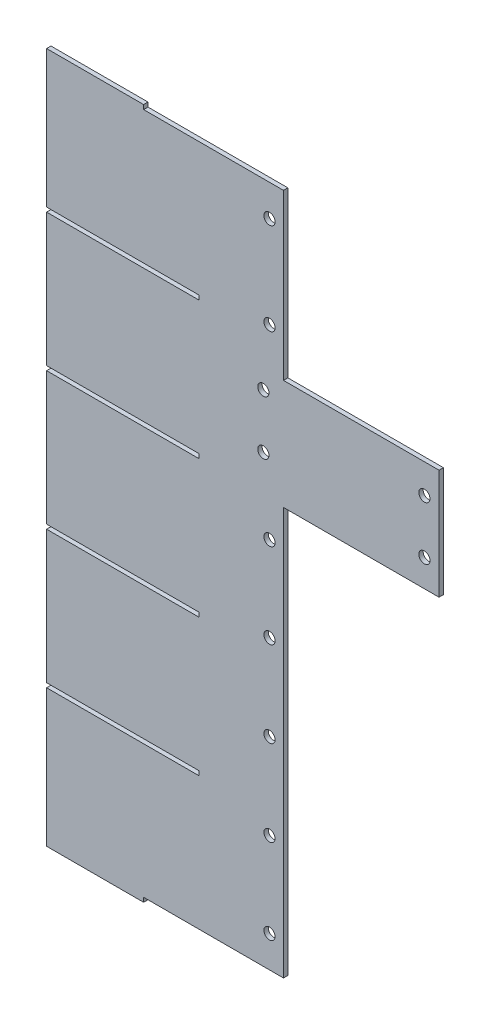
SolidWorks part; units mm, degrees
material "6061-T6 (SS)"
ref_plane "X-Y Datum" through (0, 0, 0) normal (0, 0, 1) x (1, 0, 0)
ref_plane "X-Z Datum" through (0, 0, 0) normal (0, 1, 0) x (1, 0, 0)
ref_plane "Y-Z Datum" through (0, 0, 0) normal (1, 0, 0) x (0, 0, -1)
sketch "Sketch1" plane through (0, 0, 0) normal (0, 0, 1) x (1, 0, 0)
  line L1 (129.0131, 254.2454) -> (-18.6854, 254.2454)
  line L3 (129.0131, -241.3467) -> (-18.6854, -241.3467)
  line L4 (-18.6854, 254.2454) -> (-18.6854, 157.667)
  line L24 (129.0131, 254.2454) -> (129.0131, -241.3467)
  line L25 (92.0885, 157.667) -> (-18.6854, 157.667)
  line L27 (92.0885, 154.492) -> (-18.6854, 154.492)
  line L29 (92.0885, 57.9136) -> (-18.6854, 57.9136)
  line L31 (92.0885, 54.7386) -> (-18.6854, 54.7386)
  line L33 (92.0885, -41.8399) -> (-18.6854, -41.8399)
  line L35 (92.0885, -45.0149) -> (-18.6854, -45.0149)
  line L37 (92.0885, -141.5933) -> (-18.6854, -141.5933)
  line L39 (92.0885, -144.7683) -> (-18.6854, -144.7683)
  line L41 (92.0885, -141.5933) -> (92.0885, -144.7683)
  line L42 (92.0885, -41.8399) -> (92.0885, -45.0149)
  line L43 (92.0885, 57.9136) -> (92.0885, 54.7386)
  line L44 (-18.6854, -144.7683) -> (-18.6854, -241.3467)
  line L45 (-18.6854, -45.0149) -> (-18.6854, -141.5933)
  line L46 (-18.6854, 54.7386) -> (-18.6854, -41.8399)
  line L47 (-18.6854, 154.492) -> (-18.6854, 57.9136)
  line L48 (92.0885, 157.667) -> (92.0885, 154.492)
extrude "Boss-Extrude2" add sketch "Sketch1" along normal blind 3.175
sketch "Sketch4" plane through (0, 0, 3.175) normal (0, 0, 1) x (1, 0, 0)
  line L0 (129.0131, 254.2454) -> (153.4072, 240.1614) construction
  line L2 (129.0131, 254.2454) -> (129.0131, -241.3467)
  line L4 (153.4072, 240.1614) -> (153.4072, -227.2627)
  line L6 (153.4072, -227.2627) -> (153.4072, -241.3467)
  line L7 (153.4072, -241.3467) -> (129.0131, -241.3467)
  line L8 (129.0131, 254.2454) -> (153.4072, 254.2454)
  line L9 (153.4072, 254.2454) -> (153.4072, 240.1614)
extrude "Boss-Extrude3" add sketch "Sketch4" against normal through all
sketch "Sketch7" plane through (0, 0, 3.175) normal (0, 0, 1) x (1, 0, 0)
  line L0 (51.8072, -241.3467) -> (-18.6854, -241.3467)
  line L1 (51.8072, -244.5217) -> (51.8072, -241.3467)
  line L2 (153.4072, -244.5217) -> (51.8072, -244.5217)
  line L3 (153.4072, -244.5217) -> (153.4072, -257.2217)
  line L4 (153.4072, -257.2217) -> (30.4963, -257.2217)
  line L5 (30.4963, -257.2217) -> (6.7146, -273.4777)
  line L6 (-18.6854, -273.4777) -> (6.7146, -273.4777)
  line L7 (-18.6854, -241.3467) -> (-18.6854, -273.4777)
  point P0 (-51.634, -260.9767)
  point P9 (-18.6854, -241.3467)
extrude "Boss-Extrude6" [suppressed] add sketch "Sketch7" against normal through all
sketch "Sketch8" [suppressed] plane through (0, 0, 3.175) normal (0, 0, 1) x (1, 0, 0)
  line L1 (153.4072, -257.2217) -> (221.7231, -257.2217)
  line L2 (153.4072, -257.2217) -> (153.4072, -244.5217)
  line L3 (153.4072, -244.5217) -> (221.7231, -244.5217)
  line L4 (221.7231, -257.2217) -> (221.7231, -244.5217)
  line L5 (153.4072, -241.3467) -> (221.7231, -241.3467)
  line L6 (153.4072, -241.3467) -> (153.4072, -144.7683)
  line L7 (153.4072, -144.7683) -> (221.7231, -144.7683)
  line L8 (221.7231, -241.3467) -> (221.7231, -144.7683)
  dimension "D1" = 68.3158
extrude "Boss-Extrude7" [suppressed] add sketch "Sketch8" against normal through all
sketch "Sketch11" plane through (0, 0, 3.175) normal (0, 0, 1) x (1, 0, 0)
  line L0 (92.0885, 54.7386) -> (153.4072, 54.7386) construction
  line L1 (153.4072, 134.68) -> (266.4372, 134.68)
  line L2 (153.4072, -241.3467) -> (153.4072, 254.2454) construction
  line L3 (266.4372, 134.68) -> (266.4372, 54.7386)
  line L4 (266.4372, 54.7386) -> (153.4072, 54.7386)
  line L5 (153.4072, 54.7386) -> (153.4072, 134.68)
  line L6 (153.4072, -241.3467) -> (153.4072, 254.2454) construction
extrude "Boss-Extrude8" add sketch "Sketch11" against normal through all
sketch "Sketch12" plane through (0, 0, 0) normal (0, 0, -1) x (-1, 0, 0)
  line L1 (18.6854, 254.2454) -> (-51.8072, 254.2454)
  line L2 (18.6854, 254.2454) -> (18.6854, 257.4204)
  line L3 (18.6854, 257.4204) -> (-51.8072, 257.4204)
  line L4 (-51.8072, 254.2454) -> (-51.8072, 257.4204)
  line L5 (18.6854, -241.3467) -> (-51.8072, -241.3467)
  line L6 (18.6854, -241.3467) -> (18.6854, -244.5217)
  line L7 (18.6854, -244.5217) -> (-51.8072, -244.5217)
  line L8 (-51.8072, -241.3467) -> (-51.8072, -244.5217)
extrude "Boss-Extrude9" add sketch "Sketch12" against normal through all
sketch "Sketch14" plane through (0, 0, 3.175) normal (0, 0, 1) x (1, 0, 0)
  line L0 (-18.6854, -244.5217) -> (269.694, -244.5217)
  line L1 (-18.6854, -244.5217) -> (-18.6854, 277.9004)
  line L2 (-18.6854, 277.9004) -> (269.694, 277.9004)
  line L3 (269.694, -244.5217) -> (269.694, 277.9004)
  point P0 (143.2472, -231.1146)
  point P1 (143.2472, -158.2226)
  point P2 (143.2472, -85.3305)
  point P3 (143.2472, -12.4385)
  point P4 (143.2472, 60.4536)
  point P5 (170.6792, 87.8856)
  point P6 (210.7117, 87.8856)
  point P7 (250.7441, 87.8856)
  point P8 (256.2772, 93.4187)
  point P9 (256.2772, 119.6462)
  point P10 (256.2772, 145.8738)
  point P11 (143.2472, 173.5725)
  point P12 (143.2472, 208.7929)
  point P13 (143.2472, 244.0133)
sketch "Sketch15" plane through (0, 0, 3.175) normal (0, 0, 1) x (1, 0, 0)
  line L0 (-18.6854, 257.4204) -> (23.3644, 257.4204) construction
  line L1 (-18.6854, 257.4204) -> (-18.6854, 239.7041) construction
  line L2 (-18.6854, 239.7041) -> (23.3644, 239.7041) construction
  line L3 (23.3644, 257.4204) -> (23.3644, 239.7041) construction
  line L4 (258.5632, 130.1671) -> (255.7997, 130.1671) construction
  line L5 (255.7997, 130.1671) -> (255.7997, 113.344) construction
  circle A0 centre (143.2472, 231.3133) radius 4.064
  circle A1 centre (143.2472, 164.652) radius 4.064
  circle A2 centre (255.7997, 113.344) radius 4.064
  circle A3 centre (255.7997, 74.4957) radius 4.064
  circle A4 centre (143.2472, 29.3386) radius 4.064
  circle A5 centre (143.2472, -32.3342) radius 4.064
  circle A6 centre (143.2472, -94.538) radius 4.064
  circle A7 centre (143.2472, -156.7418) radius 4.064
  circle A8 centre (143.2472, -218.4146) radius 4.064
  point P0 (143.2472, 231.3133)
  point P1 (143.2472, 164.652)
  point P2 (255.7997, 113.344)
  point P3 (255.7997, 74.4957)
  point P4 (143.2472, 29.3386)
  point P5 (143.2472, -32.3342)
  point P6 (143.2472, -94.538)
  point P7 (143.2472, -156.7418)
  point P8 (143.2472, -218.4146)
  point P13 (-18.6854, 257.4204)
  point P35 (255.7997, 74.4957)
extrude "Cut-Extrude1" cut sketch "Sketch15" against normal through all
sketch "Sketch16" plane through (0, 0, 3.175) normal (0, 0, 1) x (1, 0, 0)
  line L0 (141.8421, 121.4512) -> (135.7421, 121.4512) construction
  line L1 (141.8421, 82.1409) -> (135.7421, 82.1409) construction
  line L2 (266.4372, 134.68) -> (206.1233, 134.68) construction
  line L3 (266.4372, 134.68) -> (266.4372, 101.236) construction
  line L4 (266.4372, 101.236) -> (206.1233, 101.236) construction
  line L5 (206.1233, 134.68) -> (206.1233, 101.236) construction
  circle A0 centre (138.7921, 121.4512) radius 4.064
  circle A1 centre (138.7921, 82.1409) radius 4.064
  point P12 (266.4372, 134.68)
extrude "Cut-Extrude2" cut sketch "Sketch16" against normal through all
